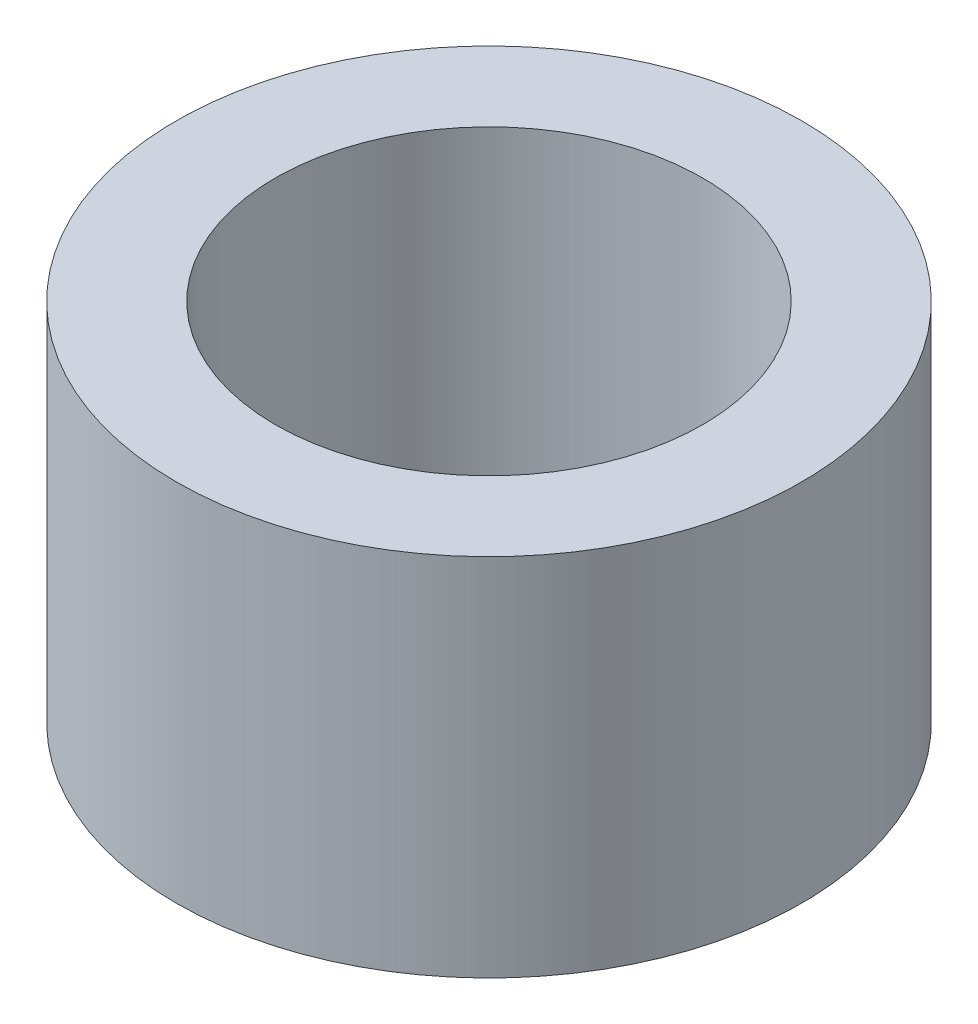
SolidWorks part; units mm, degrees
ref_plane "Front Plane" through (0, 0, 0) normal (0, 0, 1) x (1, 0, 0)
ref_plane "Top Plane" through (0, 0, 0) normal (0, 1, 0) x (1, 0, 0)
ref_plane "Right Plane" through (0, 0, 0) normal (1, 0, 0) x (0, 0, -1)
sketch "Sketch1" plane through (0, 0, 0) normal (0, 1, 0) x (1, 0, 0)
  circle A0 centre (0, 0) radius 4.1
  circle A1 centre (0, 0) radius 6
  dimension "D1" = 8.2
  dimension "D2" = 12
extrude "Boss-Extrude1" add sketch "Sketch1" along normal blind 7
